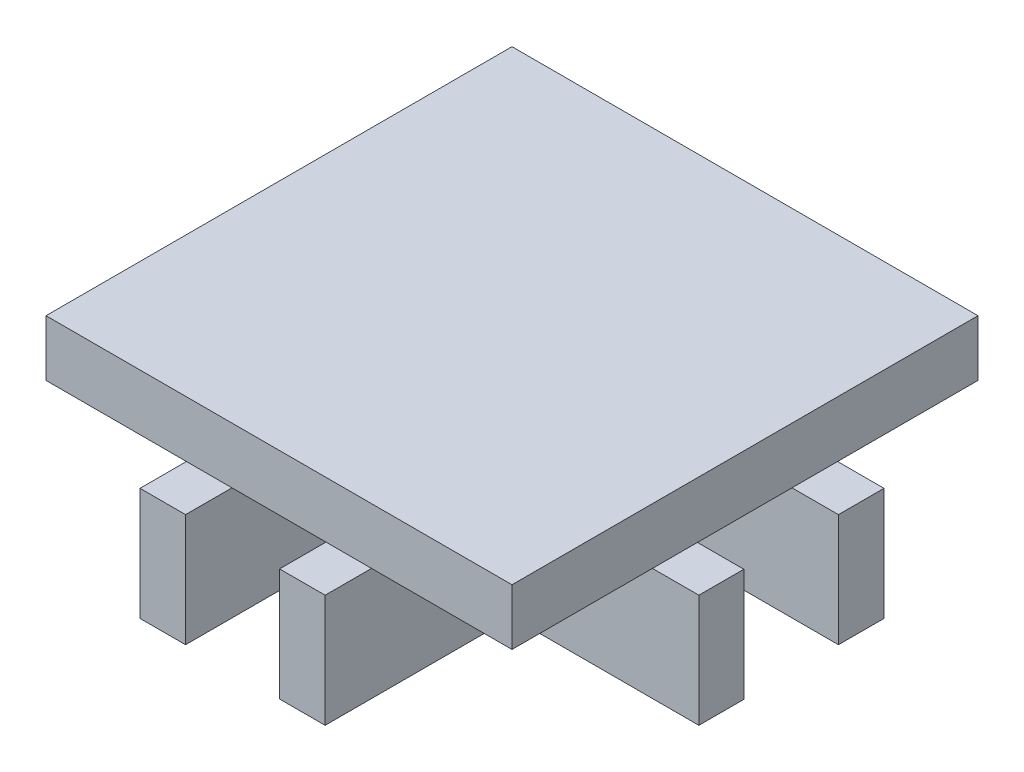
SolidWorks part; units mm, degrees
ref_plane "Front Plane" through (0, 0, 0) normal (0, 0, 1) x (1, 0, 0)
ref_plane "Top Plane" through (0, 0, 0) normal (0, 1, 0) x (1, 0, 0)
ref_plane "Right Plane" through (0, 0, 0) normal (1, 0, 0) x (0, 0, -1)
sketch "Sketch1" plane through (0, 0, 0) normal (0, 1, 0) x (1, 0, 0)
  line L1 (-40.432, 34.9347) -> (39.368, 34.9347)
  line L2 (-40.432, 34.9347) -> (-40.432, -44.8653)
  line L3 (-40.432, -44.8653) -> (39.368, -44.8653)
  line L4 (39.368, 34.9347) -> (39.368, -44.8653)
  dimension "D1" = 79.8
  dimension "D2" = 79.8
extrude "Boss-Extrude1" add sketch "Sketch1" along normal blind 9.6 contours L4 L3 L2 L1
sketch "Sketch3" plane through (0, 0, 0) normal (0, -1, 0) x (1, 0, 0)
  line L0 (-46.5398, 20.8153) -> (47.318, 20.8153)
  line L1 (-16.382, 20.8153) -> (15.318, 20.8153)
  line L2 (-16.382, 20.8153) -> (-16.382, -10.8847)
  line L3 (-16.382, -10.8847) -> (15.318, -10.8847)
  line L4 (15.318, 20.8153) -> (15.318, -10.8847)
  line L9 (-48.382, -3.0847) -> (47.318, -3.0847)
  line L10 (-48.382, -3.0847) -> (-48.382, -10.8847)
  line L11 (-48.382, -10.8847) -> (47.318, -10.8847)
  line L12 (47.318, -3.0847) -> (47.318, -10.8847)
  line L13 (-46.5398, 20.8153) -> (-46.5398, 13.1153)
  line L14 (-46.5398, 13.1153) -> (47.318, 13.1153)
  line L15 (47.318, 20.8153) -> (47.318, 13.1153)
  line L24 (39.368, -34.9347) -> (39.368, 44.8653) construction
  line L25 (-40.432, -34.9347) -> (39.368, -34.9347) construction
  line L26 (7.518, 25.419) -> (7.518, -6.281)
  line L27 (-16.382, 52.8153) -> (-8.582, 52.8153)
  line L28 (-16.382, 52.8153) -> (-16.382, -42.8847)
  line L29 (-16.382, -42.8847) -> (-8.582, -42.8847)
  line L30 (-8.582, 52.8153) -> (-8.582, -42.8847)
  line L31 (7.518, 52.8153) -> (15.318, 52.8153)
  line L32 (7.518, 52.8153) -> (7.518, -42.8847)
  line L33 (7.518, -42.8847) -> (15.318, -42.8847)
  line L34 (15.318, 52.8153) -> (15.318, -42.8847)
  dimension "D1" = 31.7
  dimension "D2" = 31.7
  dimension "D3" = 95.7
  dimension "D4" = 7.8
  dimension "D5" = 32
  dimension "D6" = 95.7
  dimension "D7" = 32
  dimension "D8" = 95.7
  dimension "D9" = 16.2
  dimension "D10" = 7.8
  dimension "D11" = 7.8
  dimension "D12" = 32
  dimension "D13" = 24.05
  dimension "D14" = 24.05
extrude "Boss-Extrude2" add sketch "Sketch3" along normal blind 19.3 contours L1 L26 L14 L4 | L1 L30 L14 L26 | L14 L30 L9 L26 | L30 L0 L2 L14 | L11 L14 L2 L0 | L30 L12 L28 L0 | L34 L12 L32 L1 | L34 L31 L32 L12 | L30 L27 L28 L12 | L13 L14 L11 L0 | L15 L0 L9 L14 | L4 L14 L9 L0 | L14 L26 L9 L4 | L30 L14 L2 L9 | L30 L9 L2 L3 | L11 L2 L9 | L10 L11 L9 | L9 L30 L11 L26 | L9 L26 L11 L4 | L34 L11 L32 L10 | L4 L11 L9 | L12 L9 L11 | L34 L10 L32 L33 | L30 L3 L28 L10 | L30 L10 L28 L29
